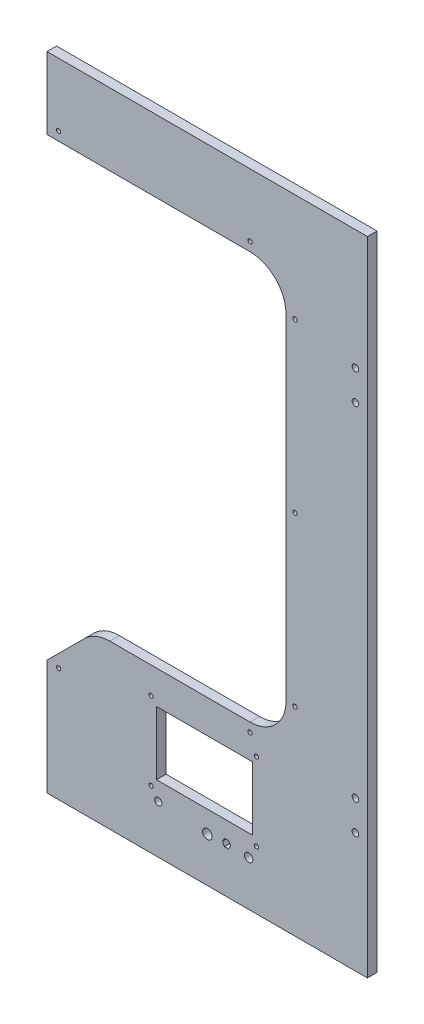
SolidWorks part; units mm, degrees
ref_plane "Front Plane" through (0, 0, 0) normal (0, 0, 1) x (1, 0, 0)
ref_plane "Top Plane" through (0, 0, 0) normal (0, 1, 0) x (1, 0, 0)
ref_plane "Right Plane" through (0, 0, 0) normal (1, 0, 0) x (0, 0, -1)
sketch "Sketch1" plane through (0, 0, 0) normal (0, 0, 1) x (1, 0, 0)
  line L0 (0, -1000) -> (0, 49000) construction
  line L10 (257.5093, -257.9907) -> (0, -257.9907) construction
  line L11 (-1000, 0) -> (49000, 0) construction
  line L12 (257.5093, 257.9907) -> (257.5093, -257.9907) construction
  line L13 (257.5093, 257.9907) -> (0, 257.9907) construction
  line L14 (267.5, -268) -> (0, 0) construction
  line L15 (267.5, 268) -> (0, 0) construction
  line L16 (0, -268) -> (0, 268)
  line L17 (267.5, -268) -> (0, -268)
  line L18 (267.5, 268) -> (267.5, -268)
  line L19 (267.5, 268) -> (0, 268)
  circle A0 centre (257.5, -168) radius 2.75
  circle A1 centre (257.5093, -143) radius 2.75
  circle A2 centre (257.5093, 143) radius 2.75
  circle A4 centre (257.5, 168) radius 2.75
  dimension "D3" = 267.5
  dimension "D1" = 25
  dimension "D2" = 100
  dimension "D4" = 536
extrude "Boss-Extrude1" add sketch "Sketch1" against normal blind 8
sketch "Sketch3" plane through (0, 0, 0) normal (0, 0, 1) x (1, 0, 0)
  line L0 (0, -268) -> (267.5, -268) construction
  line L1 (267.5, 268) -> (0, 268) construction
  line L2 (267.5, -268) -> (267.5, 268) construction
  line L3 (0, 208) -> (0, -172)
  line L4 (0, 208) -> (169.5, 208)
  line L5 (199.5, 178) -> (199.5, -102)
  line L6 (169.5, -132) -> (52.4357, -132)
  line L7 (31.2257, -140.7836) -> (0, -172)
  line L9 (153.3422, -229.7084) -> (151.6102, -226.7084)
  line L10 (151.6102, -226.7084) -> (148.146, -226.7084)
  line L11 (148.146, -226.7084) -> (146.414, -229.7084)
  line L12 (146.414, -229.7084) -> (148.146, -232.7084)
  line L13 (148.146, -232.7084) -> (151.6102, -232.7084)
  line L14 (151.6102, -232.7084) -> (153.3422, -229.7084)
  line L36 (171.3781, -212.7084) -> (171.3781, -159.7084)
  line L37 (91.3781, -212.7084) -> (171.3781, -212.7084)
  line L38 (91.3781, -159.7084) -> (91.3781, -212.7084)
  line L39 (171.3781, -159.7084) -> (91.3781, -159.7084)
  circle A0 centre (257.5093, -143) radius 2.75
  circle A1 centre (257.5, -168) radius 2.75
  arc A2 (52.4357, -132) -> (31.2257, -140.7836) centre (52.4357, -162) ccw
  arc A3 (199.5, -102) -> (169.5, -132) centre (169.5, -102) cw
  arc A4 (169.5, 208) -> (199.5, 178) centre (169.5, 178) cw
  circle A5 centre (86.8781, -154.2084) radius 1.75
  circle A6 centre (174.8781, -154.2084) radius 1.75
  circle A7 centre (174.8781, -219.2084) radius 1.75
  circle A8 centre (86.8781, -219.2084) radius 1.75
  circle A9 centre (168.3781, -230.4584) radius 3.5
  circle A10 centre (133.8781, -230.7084) radius 4
  circle A11 centre (92.8781, -227.7084) radius 3
  circle A12 centre (149.8781, -229.7084) radius 3 construction
  dimension "D7" = 30
  dimension "D4" = 3.5
  dimension "D6" = 6
  dimension "D1" = 96
  dimension "D2" = 60
  dimension "D3" = 68
  dimension "D5" = 40
extrude "Cut-Extrude3" cut sketch "Sketch3" against normal through all
sketch "Sketch4" plane through (0, 0, 0) normal (0, 0, 1) x (1, 0, 0)
  circle A0 centre (9.7264, -172.8815) radius 1.75
  circle A1 centre (169.5, -139.5) radius 1.787
  circle A2 centre (207, -102) radius 1.75
  circle A3 centre (207, 38) radius 1.75
  circle A4 centre (207, 178) radius 1.75
  circle A5 centre (169.5, 215.5) radius 1.75
  circle A6 centre (9.7264, 215.5) radius 1.75
extrude "Cut-Extrude4" cut sketch "Sketch4" against normal blind 10
